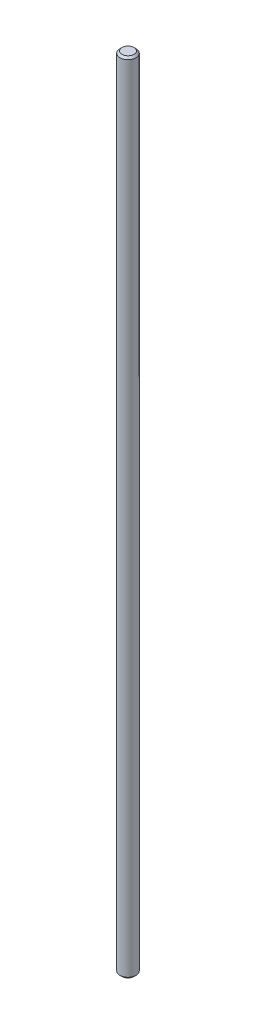
SolidWorks part; units mm, degrees
ref_plane "前基準面" through (0, 0, 0) normal (0, 0, 1) x (1, 0, 0)
ref_plane "上基準面" through (0, 0, 0) normal (0, 1, 0) x (1, 0, 0)
ref_plane "右基準面" through (0, 0, 0) normal (1, 0, 0) x (0, 0, -1)
sketch "草圖1" plane through (0, 0, 0) normal (0, 1, 0) x (1, 0, 0)
  circle A0 centre (0, 0) radius 4000
  dimension "D1" = 8000
extrude "填料-伸長1" add sketch "草圖1" along normal blind 400000
chamfer "導角1" distance 1000 angle 45 2 edges at (0, 0, 4000) (0, 400000, 4000)
